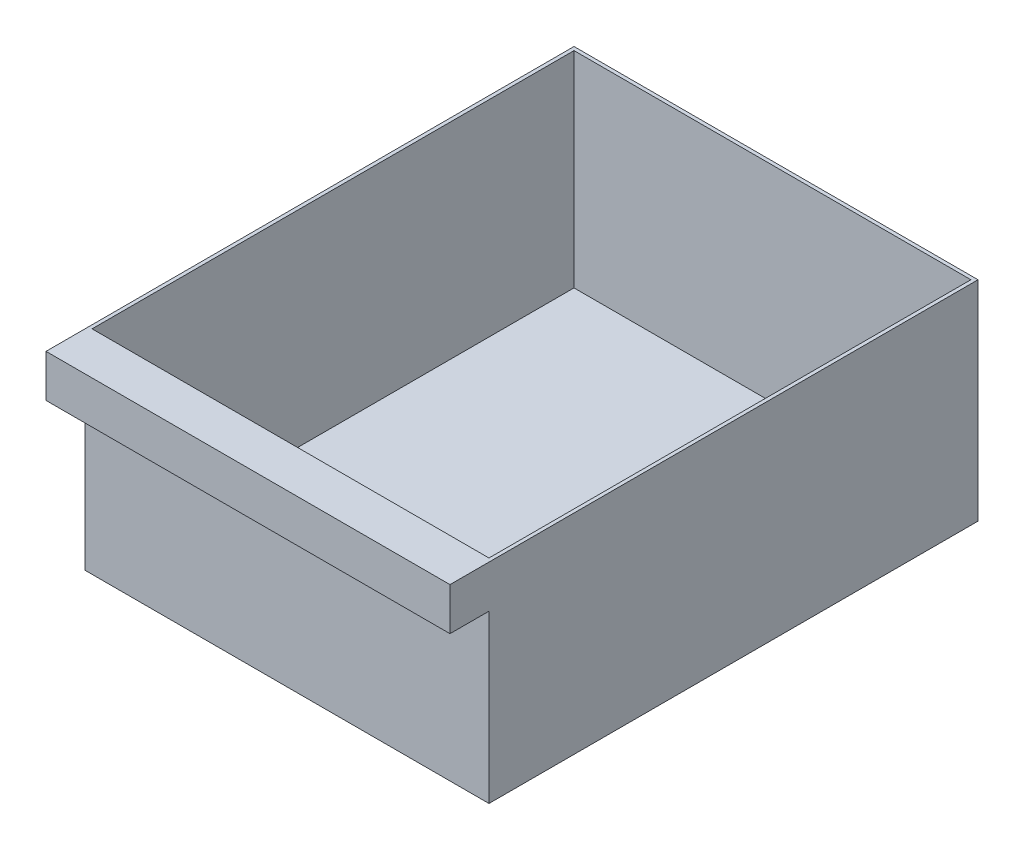
SolidWorks part; units mm, degrees
ref_plane "前视基准面" through (0, 0, 0) normal (0, 0, 1) x (1, 0, 0)
ref_plane "上视基准面" through (0, 0, 0) normal (0, 1, 0) x (1, 0, 0)
ref_plane "右视基准面" through (0, 0, 0) normal (1, 0, 0) x (0, 0, -1)
other "Configuration Table"
sketch "草图4" plane through (0, 0, 0) normal (0, 1, 0) x (1, 0, 0)
  line L6 (-57, -69) -> (57, -69)
  line L11 (-57, -69) -> (-57, 69)
  line L12 (-57, 69) -> (57, 69)
  line L13 (57, -69) -> (57, 69)
  line L14 (-57, -69) -> (57, 69) construction
  line L15 (-57, 69) -> (57, -69) construction
  point P0 (0, 0)
  dimension "D1" = 114
  dimension "D2" = 138
extrude "凸台-拉伸1" add sketch "草图4" along normal blind 59
shell "抽壳1" thickness 1
sketch "草图5" plane through (0, 0, 69) normal (0, 0, 1) x (1, 0, 0)
  line L0 (57, 59) -> (57, 0) construction
  line L1 (-57, 59) -> (57, 59)
  line L2 (-57, 59) -> (-57, 47)
  line L3 (-57, 47) -> (57, 47)
  line L4 (57, 59) -> (57, 47)
  dimension "D1" = 12
extrude "凸台-拉伸2" add sketch "草图5" along normal blind 11
sketch "草图6" plane through (0, 47, 0) normal (0, -1, 0) x (1, 0, 0)
  line L0 (-57, 80) -> (57, 80) construction
  line L1 (-56, 79) -> (56, 79)
  line L2 (-56, 79) -> (-56, 69)
  line L3 (-56, 69) -> (56, 69)
  line L4 (56, 79) -> (56, 69)
  line L5 (57, 80) -> (57, 69) construction
  line L6 (-57, 80) -> (-57, 69) construction
  line L9 (-57, 69) -> (57, 69) construction
  dimension "D1" = 1
  dimension "D2" = 1
  dimension "D3" = 1
extrude "切除-拉伸1" cut sketch "草图6" against normal offset from surface (11 mm away) 1 up to face at (0, 59, 5.5)
